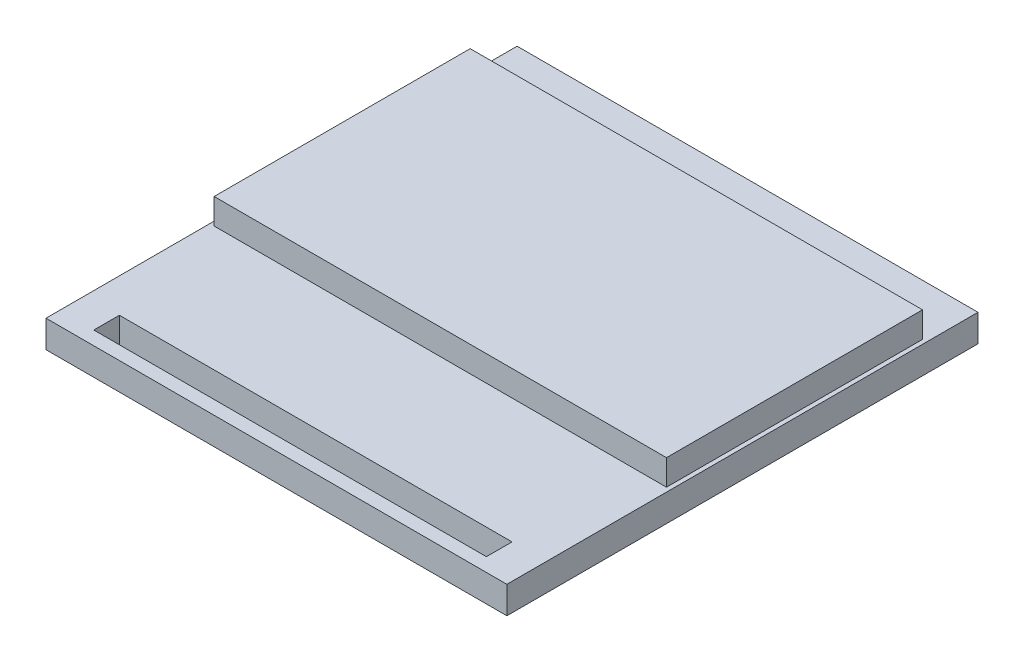
SolidWorks part; units mm, degrees
ref_plane "前视基准面" through (0, 0, 0) normal (0, 0, 1) x (1, 0, 0)
ref_plane "上视基准面" through (0, 0, 0) normal (0, 1, 0) x (1, 0, 0)
ref_plane "右视基准面" through (0, 0, 0) normal (1, 0, 0) x (0, 0, -1)
sketch "草图1" plane through (0, 0, 0) normal (0, 1, 0) x (1, 0, 0)
  line L1 (0, 0) -> (27, 0)
  line L2 (0, 0) -> (0, -27.6)
  line L3 (0, -27.6) -> (27, -27.6)
  line L4 (27, 0) -> (27, -27.6)
  line L5 (2, -26.8) -> (25, -26.8)
  line L6 (2, -26.8) -> (2, -25.3)
  line L7 (2, -25.3) -> (25, -25.3)
  line L8 (25, -26.8) -> (25, -25.3)
  dimension "D1" = 27
  dimension "D2" = 27.6
  dimension "D3" = 2
  dimension "D4" = 0.8
  dimension "D5" = 1.5
  dimension "D6" = 23
extrude "凸台-拉伸1" add sketch "草图1" along normal blind 1.6
sketch "草图2" plane through (0, 1.6, 0) normal (0, 1, 0) x (1, 0, 0)
  line L0 (27, 0) -> (0, 0) construction
  line L1 (0.25, -3) -> (26.75, -3)
  line L2 (0.25, -3) -> (0.25, -18)
  line L3 (0.25, -18) -> (26.75, -18)
  line L4 (26.75, -3) -> (26.75, -18)
  line L5 (0, 0) -> (0, -27.6) construction
  dimension "D1" = 26.5
  dimension "D2" = 15
  dimension "D3" = 3
  dimension "D4" = 0.25
extrude "凸台-拉伸2" add sketch "草图2" along normal blind 1.5
sketch "草图3" plane through (0, 0, 0) normal (0, -1, 0) x (1, 0, 0)
  line L0 (0, 0) -> (0, 27.6) construction
  line L1 (0.5, 0.6) -> (6.1, 0.6)
  line L2 (0.5, 0.6) -> (0.5, 13.2)
  line L3 (0.5, 13.2) -> (6.1, 13.2)
  line L4 (6.1, 0.6) -> (6.1, 13.2)
  line L5 (27, 0) -> (0, 0) construction
  dimension "D1" = 0.5
  dimension "D2" = 0.6
  dimension "D3" = 5.6
  dimension "D4" = 12.6
extrude "凸台-拉伸3" add sketch "草图3" along normal blind 2
sketch "草图4" plane through (0, 0, 0) normal (0, -1, 0) x (1, 0, 0)
  line L5 (27, 0) -> (0, 0) construction
  line L6 (8.4, 0) -> (18.6, 0)
  line L7 (8.4, 0) -> (8.4, 2.5)
  line L8 (8.4, 2.5) -> (18.6, 2.5)
  line L9 (18.6, 0) -> (18.6, 2.5)
  line L10 (0, 0) -> (0, 27.6) construction
  dimension "D1" = 8.4
  dimension "D2" = 2.5
  dimension "D3" = 10.2
extrude "凸台-拉伸4" add sketch "草图4" along normal blind 2.5
